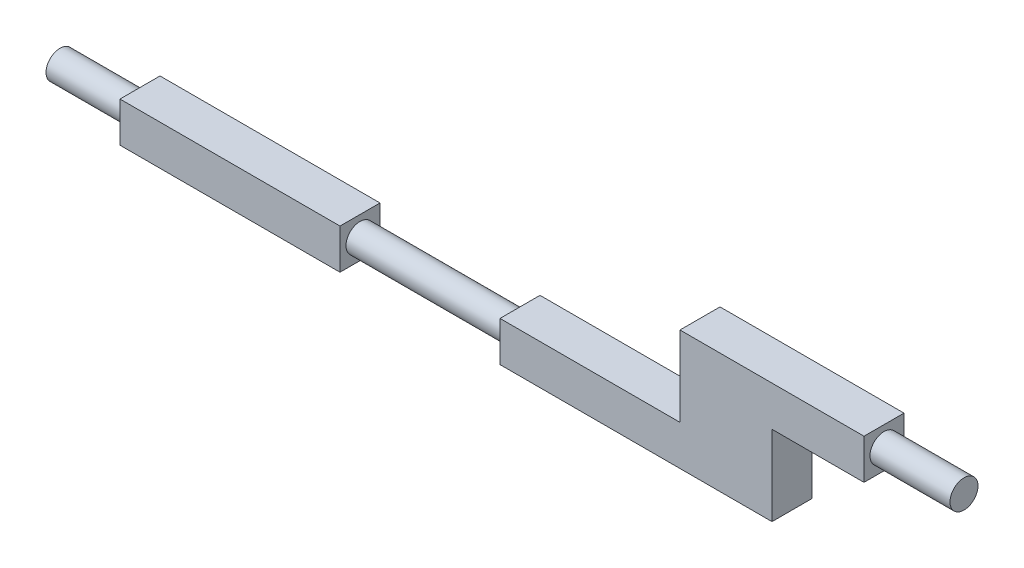
SolidWorks part; units mm, degrees
ref_plane "Front Plane" through (0, 0, 0) normal (0, 0, 1) x (1, 0, 0)
ref_plane "Top Plane" through (0, 0, 0) normal (0, 1, 0) x (1, 0, 0)
ref_plane "Right Plane" through (0, 0, 0) normal (1, 0, 0) x (0, 0, -1)
sketch "Sketch1" plane through (0, 0, 0) normal (0, 0, 1) x (1, 0, 0)
  line L0 (-66, 0) -> (0, 0)
  line L1 (0, -10) -> (-43, -10)
  line L2 (0, 0) -> (0, -10)
  line L11 (-43, -10) -> (-43, -30)
  line L12 (-43, -30) -> (-206, -30)
  line L13 (-206, -30) -> (-206, -10)
  line L14 (0, -1000) -> (0, 49000) construction
  line L15 (-206, -10) -> (-246, -10)
  line L16 (-246, -10) -> (-246, 0)
  line L17 (-246, 0) -> (-196, 0)
  line L18 (-196, 0) -> (-196, -20)
  line L19 (-196, -20) -> (-66, -20)
  line L20 (-66, -20) -> (-66, 0)
  point P3 (0, 0)
  point P4 (0, -10)
  point P12 (-196, -10)
  point P25 (-66, -10)
  dimension "D2" = 10
  dimension "D3" = 66
  dimension "D4" = 43
  dimension "D5" = 10
  dimension "D6" = 10
  dimension "D7" = 10
  dimension "D9" = 130
  dimension "D10" = 50
  dimension "D11" = 20
extrude "Boss-Extrude1" add sketch "Sketch1" along normal blind 10 contours L17 L18 L19 L20 L0 L2 L1 L11 L12 L13 L15 L16
sketch "Sketch4" plane through (0, 0, 0) normal (1, 0, 0) x (0, 0, -1)
  line L0 (-10, 0) -> (0, 0) construction
  line L1 (-10, -10) -> (-10, 0) construction
  line L3 (-10, 0) -> (0, 0)
  line L4 (-10, 0) -> (-10, -10)
  line L5 (-10, -10) -> (0, -10)
  line L6 (0, 0) -> (0, -10)
  circle A0 centre (-5, -5) radius 3.5
  point P5 (-5, 0)
  point P9 (-10, -5)
  dimension "D1" = 7
extrude "Cut-Extrude8" cut sketch "Sketch4" against normal mid plane 40
ref_plane "Plane4" through (-131, 0, 0) normal (1, 0, 0) x (0, 0, -1)
sketch "Sketch12" plane through (-131, 0, 0) normal (1, 0, 0) x (0, 0, -1)
  line L0 (0, -30) -> (0, -10) construction
  line L1 (-10, -30) -> (0, -30)
  line L2 (-10, -30) -> (-10, -20)
  line L3 (-10, -20) -> (0, -20)
  line L4 (0, -30) -> (0, -20)
  circle A0 centre (-5, -25) radius 3.5
  point P10 (-5, -20)
  point P12 (-10, -25)
  dimension "D1" = 7
extrude "Cut-Extrude10" cut sketch "Sketch12" against normal mid plane 40
sketch "Sketch14" plane through (-246, 0, 0) normal (-1, 0, 0) x (0, 0, 1)
  line L1 (0, -10) -> (10, -10)
  line L2 (0, -10) -> (0, 0)
  line L3 (0, 0) -> (10, 0)
  line L4 (10, -10) -> (10, 0)
  circle A0 centre (5, -5) radius 3.5
  point P10 (5, 0)
  point P12 (0, -5)
  dimension "D1" = 7
extrude "Cut-Extrude12" cut sketch "Sketch14" against normal blind 40
sketch "Sketch15" plane through (-206, 0, 0) normal (-1, 0, 0) x (0, 0, 1)
  line L0 (10, -30) -> (0, -30) construction
  circle A0 centre (5, -25) radius 3.5
  circle A1 centre (5, -5) radius 3.5 construction
  point P8 (5, -30)
  dimension "D1" = 5
extrude "Boss-Extrude2" add sketch "Sketch15" along normal blind 20
sketch "Sketch16" plane through (0, 0, 0) normal (0, 0, 1) x (1, 0, 0)
  line L1 (-246, -10) -> (-246, 0) construction
  line L2 (-246, 0) -> (-196, 0)
  line L3 (-246, 0) -> (-246, -20)
  line L4 (-246, -20) -> (-196, -20)
  line L5 (-196, 0) -> (-196, -20)
  line L6 (-196, -20) -> (-151, -20) construction
  line L7 (-196, 0) -> (-196, -20) construction
extrude "Cut-Extrude14" cut sketch "Sketch16" along normal blind 200
ref_plane "Plane5" through (0, 0, 5) normal (0, 0, 1) x (1, 0, 0)
sketch "Sketch17" plane through (0, 0, 5) normal (0, 0, 1) x (1, 0, 0)
  line L0 (-174.7114, -5) -> (-124.7114, -5) construction
  line L3 (-43, -30) -> (-111, -30) construction
  point P6 (-149.7114, -5)
  dimension "D1" = 50
  dimension "D2" = 25
